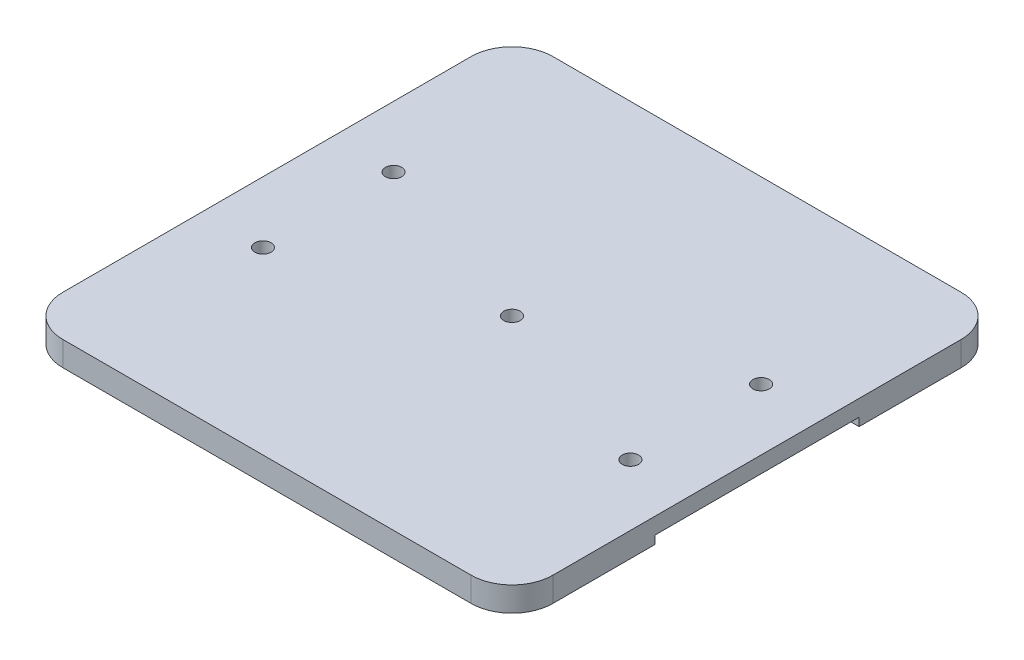
SolidWorks part; units mm, degrees
ref_plane "Front Plane" through (0, 0, 0) normal (0, 0, 1) x (1, 0, 0)
ref_plane "Top Plane" through (0, 0, 0) normal (0, 1, 0) x (1, 0, 0)
ref_plane "Right Plane" through (0, 0, 0) normal (1, 0, 0) x (0, 0, -1)
sketch "Sketch1" plane through (0, 0, 0) normal (0, 1, 0) x (1, 0, 0)
  line L1 (-32.0588, 17.8235) -> (17.9412, 17.8235)
  line L2 (-37.0588, 12.8235) -> (-37.0588, -37.1765)
  line L3 (-32.0588, -42.1765) -> (17.9412, -42.1765)
  line L4 (22.9412, 12.8235) -> (22.9412, -37.1765)
  arc A0 (17.9412, 17.8235) -> (22.9412, 12.8235) centre (17.9412, 12.8235) cw
  arc A1 (17.9412, -42.1765) -> (22.9412, -37.1765) centre (17.9412, -37.1765) ccw
  arc A2 (-37.0588, -37.1765) -> (-32.0588, -42.1765) centre (-32.0588, -37.1765) ccw
  arc A3 (-32.0588, 17.8235) -> (-37.0588, 12.8235) centre (-32.0588, 12.8235) ccw
  point P6 (22.9412, 17.8235)
  point P11 (-37.0588, -42.1765)
  point P14 (-37.0588, 17.8235)
  dimension "D3" = 5
  dimension "D1" = 60
  dimension "D2" = 60
extrude "Boss-Extrude1" add sketch "Sketch1" along normal blind 3
sketch "Sketch2" plane through (0, 0, 0) normal (0, 1, 0) x (1, 0, 0)
  line L0 (-37.0588, 12.8235) -> (-37.0588, -37.1765) construction
  line L1 (-37.0588, 0.3235) -> (-22.0588, 0.3235)
  line L2 (-37.0588, 0.3235) -> (-37.0588, -24.6765)
  line L3 (-37.0588, -24.6765) -> (-22.0588, -24.6765)
  line L4 (-22.0588, 0.3235) -> (-22.0588, -24.6765)
  line L5 (17.9412, 17.8235) -> (-32.0588, 17.8235) construction
  line L6 (7.9412, 0.3235) -> (22.9412, 0.3235)
  line L7 (7.9412, 0.3235) -> (7.9412, -24.6765)
  line L8 (7.9412, -24.6765) -> (22.9412, -24.6765)
  line L9 (22.9412, 0.3235) -> (22.9412, -24.6765)
  line L10 (22.9412, -37.1765) -> (22.9412, 12.8235) construction
  line L11 (17.9412, 17.8235) -> (-32.0588, 17.8235) construction
  dimension "D1" = 15
  dimension "D2" = 25
  dimension "D3" = 17.5
  dimension "D4" = 15
  dimension "D5" = 17.5
  dimension "D6" = 25
extrude "Cut-Extrude1" cut sketch "Sketch2" along normal blind 1
sketch "Sketch3" plane through (0, 1, 0) normal (0, -1, 0) x (-1, 0, 0)
  line L1 (37.0588, -24.6765) -> (22.0588, -24.6765) construction
  line L2 (37.0588, 0.3235) -> (37.0588, -24.6765) construction
  line L3 (22.0588, 0.3235) -> (37.0588, 0.3235) construction
  line L4 (-22.9412, -24.6765) -> (-22.9412, 0.3235) construction
  circle A4 centre (29.5588, -20.1765) radius 1
  circle A5 centre (29.5588, -4.1765) radius 1
  circle A6 centre (-15.4412, -20.1765) radius 1
  circle A7 centre (-15.4412, -4.1765) radius 1
  dimension "D1" = 4.5
  dimension "D3" = 7.5
  dimension "D5" = 7.5
  dimension "D2" = 7.5
  dimension "D4" = 4.5
extrude "Cut-Extrude2" cut sketch "Sketch3" against normal blind 2
sketch "Sketch4" plane through (0, 0, 0) normal (0, -1, 0) x (-1, 0, 0)
  line L0 (37.0588, 0.3235) -> (37.0588, -24.6765) construction
  line L1 (32.0588, -42.1765) -> (-17.9412, -42.1765) construction
  circle A0 centre (7.0588, -12.1765) radius 1
  dimension "D1" = 30
  dimension "D2" = 30
extrude "Cut-Extrude4" cut sketch "Sketch4" against normal blind 3
